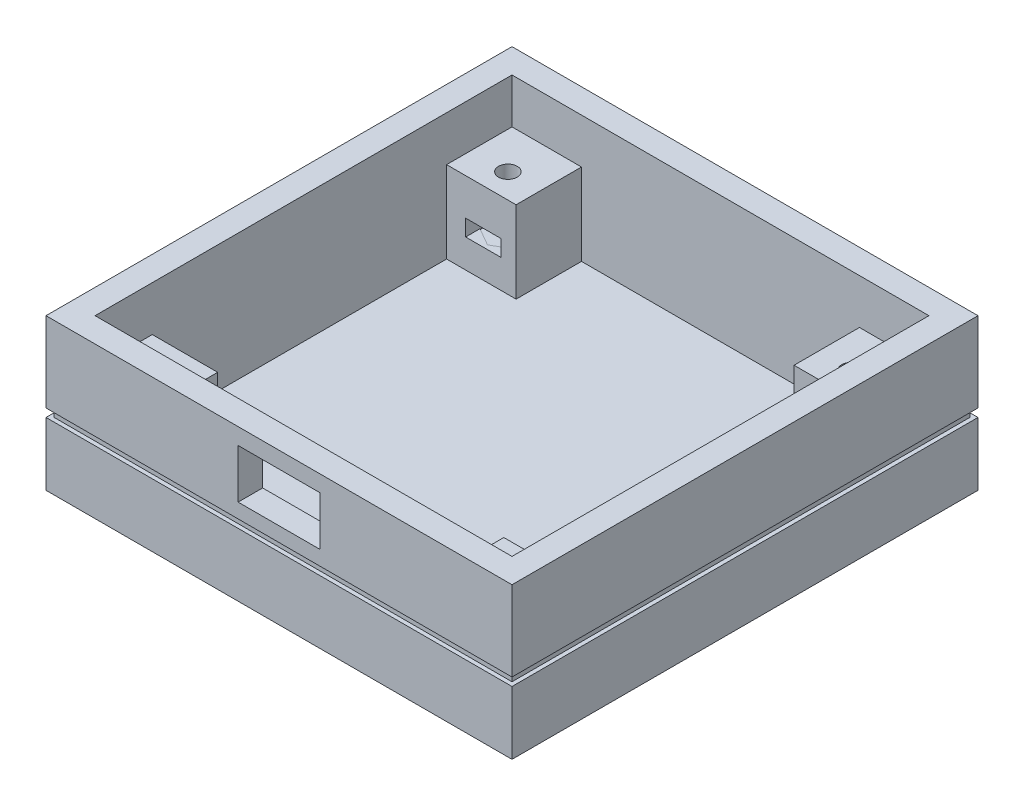
SolidWorks part; units mm, degrees
ref_plane "Plan de face" through (0, 0, 0) normal (0, 0, 1) x (1, 0, 0)
ref_plane "Plan de dessus" through (0, 0, 0) normal (0, 1, 0) x (1, 0, 0)
ref_plane "Plan de droite" through (0, 0, 0) normal (1, 0, 0) x (0, 0, -1)
sketch "Esquisse1" plane through (0, 0, 0) normal (0, 1, 0) x (1, 0, 0)
  line L1 (-30.0101, 36.8942) -> (26.9899, 36.8942)
  line L2 (-30.0101, 36.8942) -> (-30.0101, -20.1058)
  line L3 (-30.0101, -20.1058) -> (26.9899, -20.1058)
  line L4 (26.9899, 36.8942) -> (26.9899, -20.1058)
extrude "Boss.-Extru.1" add sketch "Esquisse1" along normal blind 18.5 contours L2 L3 L4 L1
sketch "Esquisse2" plane through (0, 18.5, 0) normal (0, 1, 0) x (1, 0, 0)
  line L0 (-30.0101, 36.8942) -> (26.9899, 36.8942) construction
  line L1 (-27.0101, 33.8942) -> (23.9899, 33.8942)
  line L2 (-27.0101, 33.8942) -> (-27.0101, -17.1058)
  line L3 (-27.0101, -17.1058) -> (23.9899, -17.1058)
  line L4 (23.9899, 33.8942) -> (23.9899, -17.1058)
  line L5 (-30.0101, 36.8942) -> (-30.0101, -20.1058) construction
  line L6 (26.9899, 36.8942) -> (26.9899, -20.1058) construction
  line L7 (-30.0101, -20.1058) -> (26.9899, -20.1058) construction
  dimension "D1" = 3
  dimension "D2" = 3
  dimension "D3" = 3
  dimension "D4" = 3
extrude "Enlèv. mat.-Extru.1" cut sketch "Esquisse2" against normal blind 15.5 contours L2 L3 L4 L1
sketch "Esquisse4" plane through (0, 3, 0) normal (0, 1, 0) x (1, 0, 0)
  line L1 (-18.5101, 25.8942) -> (-27.0101, 25.8942)
  line L2 (-18.5101, 25.8942) -> (-18.5101, 33.8942)
  line L3 (-18.5101, 33.8942) -> (-27.0101, 33.8942)
  line L4 (-27.0101, 25.8942) -> (-27.0101, 33.8942)
extrude "Boss.-Extru.2" add sketch "Esquisse4" along normal blind 10
sketch "Esquisse5" plane through (0, 3, 0) normal (0, 1, 0) x (1, 0, 0)
  line L1 (23.9899, 33.8942) -> (15.4899, 33.8942)
  line L2 (23.9899, 33.8942) -> (23.9899, 25.8942)
  line L3 (23.9899, 25.8942) -> (15.4899, 25.8942)
  line L4 (15.4899, 33.8942) -> (15.4899, 25.8942)
extrude "Boss.-Extru.3" add sketch "Esquisse5" along normal blind 10
sketch "Esquisse6" plane through (0, 3, 0) normal (0, 1, 0) x (1, 0, 0)
  line L1 (23.9899, -17.1058) -> (15.9899, -17.1058)
  line L2 (23.9899, -17.1058) -> (23.9899, -10.1058)
  line L3 (23.9899, -10.1058) -> (15.9899, -10.1058)
  line L4 (15.9899, -17.1058) -> (15.9899, -10.1058)
extrude "Boss.-Extru.4" add sketch "Esquisse6" along normal blind 10
sketch "Esquisse7" plane through (0, 3, 0) normal (0, 1, 0) x (1, 0, 0)
  line L1 (-19.0101, -10.1058) -> (-27.0101, -10.1058)
  line L2 (-19.0101, -10.1058) -> (-19.0101, -17.1058)
  line L3 (-19.0101, -17.1058) -> (-27.0101, -17.1058)
  line L4 (-27.0101, -10.1058) -> (-27.0101, -17.1058)
extrude "Boss.-Extru.5" add sketch "Esquisse7" along normal blind 10
sketch "Esquisse8" plane through (0, 13, 0) normal (0, 1, 0) x (1, 0, 0)
  line L0 (15.9899, -17.1058) -> (23.9899, -17.1058) construction
  line L2 (23.9899, -17.1058) -> (23.9899, -10.1058) construction
  circle A0 centre (19.4899, -13.1058) radius 1.15
  dimension "D1" = 4
  dimension "D2" = 4.5
extrude "Enlèv. mat.-Extru.2" cut sketch "Esquisse8" against normal blind 10
sketch "Esquisse9" plane through (0, 13, 0) normal (0, 1, 0) x (1, 0, 0)
  line L0 (-27.0101, -17.1058) -> (-19.0101, -17.1058) construction
  line L1 (-27.0101, -10.1058) -> (-27.0101, -17.1058) construction
  circle A0 centre (-22.5101, -13.1058) radius 1.15
  dimension "D1" = 4
  dimension "D2" = 4.5
extrude "Enlèv. mat.-Extru.3" cut sketch "Esquisse9" against normal blind 10
sketch "Esquisse16" plane through (0, 13, 0) normal (0, 1, 0) x (1, 0, 0)
  line L0 (-18.5101, 33.8942) -> (-27.0101, 33.8942) construction
  line L1 (-27.0101, 33.8942) -> (-27.0101, 25.8942) construction
  circle A0 centre (-22.5101, 28.8942) radius 1.15
  dimension "D1" = 5
  dimension "D2" = 4.5
extrude "Enlèv. mat.-Extru.9" cut sketch "Esquisse16" against normal blind 6.6 contours A0
sketch "Esquisse17" plane through (0, 13, 0) normal (0, 1, 0) x (1, 0, 0)
  line L0 (23.9899, 33.8942) -> (15.4899, 33.8942) construction
  line L1 (23.9899, 25.8942) -> (23.9899, 33.8942) construction
  circle A0 centre (19.4899, 28.8942) radius 1.15
  dimension "D1" = 5
  dimension "D2" = 4.5
extrude "Enlèv. mat.-Extru.10" cut sketch "Esquisse17" against normal blind 10
sketch "Esquisse21" plane through (0, 0, 20.1058) normal (0, 0, 1) x (1, 0, 0)
  line L0 (-30.0101, 0) -> (26.9899, 0) construction
  line L1 (-6.5101, 16.5) -> (3.4899, 16.5)
  line L2 (-6.5101, 16.5) -> (-6.5101, 10.5)
  line L3 (-6.5101, 10.5) -> (3.4899, 10.5)
  line L4 (3.4899, 16.5) -> (3.4899, 10.5)
  line L5 (-30.0101, 18.5) -> (-30.0101, 0) construction
  line L7 (26.9899, 18.5) -> (26.9899, 0) construction
  dimension "D1" = 10.5
  dimension "D2" = 23.5
  dimension "D3" = 23.5
extrude "Enlèv. mat.-Extru.14" cut sketch "Esquisse21" against normal blind 3
sketch "Esquisse23" plane through (0, 0, -25.8942) normal (0, 0, 1) x (1, 0, 0)
  line L0 (15.4899, 13) -> (15.4899, 3) construction
  line L5 (21.6599, 5) -> (17.3199, 5)
  line L6 (21.6599, 5) -> (21.6599, 3)
  line L7 (21.6599, 3) -> (17.3199, 3)
  line L8 (17.3199, 5) -> (17.3199, 3)
  line L9 (23.9899, 13) -> (23.9899, 3) construction
  dimension "D1" = 1.83
  dimension "D2" = 2.33
sketch "Esquisse24" plane through (0, 13, 0) normal (0, 1, 0) x (1, 0, 0)
  line L1 (19.4899, 26.3942) -> (21.655, 27.6442)
  line L2 (21.655, 27.6442) -> (21.655, 30.1442)
  line L3 (21.655, 30.1442) -> (19.4899, 31.3942)
  line L4 (19.4899, 31.3942) -> (17.3249, 30.1442)
  line L5 (17.3249, 30.1442) -> (17.3249, 27.6442)
  line L6 (17.3249, 27.6442) -> (19.4899, 26.3942)
  circle A0 centre (19.4899, 28.8942) radius 2.1651 construction
  circle A1 centre (19.4899, 28.8942) radius 1.15 construction
  dimension "D1" = 0
extrude "Enlèv. mat.-Extru.18" cut sketch "Esquisse24" against normal blind 2 from offset 8 contours L1 L2 L3 L4 L5 L6 offset against normal yes
sketch "Esquisse25" plane through (0, 13, 0) normal (0, 1, 0) x (1, 0, 0)
  line L1 (17.3249, -11.8558) -> (17.3249, -14.3558)
  line L2 (17.3249, -14.3558) -> (19.4899, -15.6058)
  line L3 (19.4899, -15.6058) -> (21.655, -14.3558)
  line L4 (21.655, -14.3558) -> (21.655, -11.8558)
  line L5 (21.655, -11.8558) -> (19.4899, -10.6058)
  line L6 (19.4899, -10.6058) -> (17.3249, -11.8558)
  circle A0 centre (19.4899, -13.1058) radius 2.1651 construction
  circle A1 centre (19.4899, -13.1058) radius 1.15 construction
  dimension "D1" = 0
extrude "Enlèv. mat.-Extru.20" cut sketch "Esquisse25" against normal blind 2 from offset 8 offset against normal yes
sketch "Esquisse26" plane through (0, 0, 10.1058) normal (0, 0, -1) x (-1, 0, 0)
  line L0 (-15.9899, 13) -> (-15.9899, 3) construction
  line L1 (-21.6599, 5) -> (-17.3199, 5)
  line L2 (-21.6599, 5) -> (-21.6599, 3)
  line L3 (-21.6599, 3) -> (-17.3199, 3)
  line L4 (-17.3199, 5) -> (-17.3199, 3)
  line L5 (-23.9899, 13) -> (-23.9899, 3) construction
  dimension "D1" = 1.33
  dimension "D2" = 2.33
extrude "Enlèv. mat.-Extru.21" cut sketch "Esquisse26" against normal blind 2.848
sketch "Esquisse27" plane through (0, 13, 0) normal (0, 1, 0) x (1, 0, 0)
  line L1 (-20.345, 27.6442) -> (-20.345, 30.1442)
  line L2 (-20.345, 30.1442) -> (-22.5101, 31.3942)
  line L3 (-22.5101, 31.3942) -> (-24.6751, 30.1442)
  line L4 (-24.6751, 30.1442) -> (-24.6751, 27.6442)
  line L5 (-24.6751, 27.6442) -> (-22.5101, 26.3942)
  line L6 (-22.5101, 26.3942) -> (-20.345, 27.6442)
  circle A0 centre (-22.5101, 28.8942) radius 2.1651 construction
  circle A1 centre (-22.5101, 28.8942) radius 1.15 construction
  dimension "D1" = 0
  dimension "D2" = 0
extrude "Enlèv. mat.-Extru.22" cut sketch "Esquisse27" against normal blind 2.1 from offset 4.5 contours L4 L5 L6 L1 L2 L3 offset against normal yes
sketch "Esquisse29" plane through (0, 13, 0) normal (0, 1, 0) x (1, 0, 0)
  line L1 (-20.345, -11.8558) -> (-22.5101, -10.6058)
  line L2 (-22.5101, -10.6058) -> (-24.6751, -11.8558)
  line L3 (-24.6751, -11.8558) -> (-24.6751, -14.3558)
  line L4 (-24.6751, -14.3558) -> (-22.5101, -15.6058)
  line L5 (-22.5101, -15.6058) -> (-20.345, -14.3558)
  line L6 (-20.345, -14.3558) -> (-20.345, -11.8558)
  circle A0 centre (-22.5101, -13.1058) radius 2.1651 construction
  circle A1 centre (-22.5101, -13.1058) radius 1.15 construction
  dimension "D1" = 0
extrude "Enlèv. mat.-Extru.24" cut sketch "Esquisse29" against normal blind 2 from offset 8 offset against normal yes
sketch "Esquisse30" plane through (0, 0, 10.1058) normal (0, 0, -1) x (-1, 0, 0)
  line L0 (19.0101, 13) -> (19.0101, 3) construction
  line L1 (24.6801, 5) -> (20.3401, 5)
  line L2 (24.6801, 5) -> (24.6801, 3)
  line L3 (24.6801, 3) -> (20.3401, 3)
  line L4 (20.3401, 5) -> (20.3401, 3)
  line L5 (27.0101, 13) -> (27.0101, 3) construction
  dimension "D1" = 1.33
  dimension "D2" = 2.33
extrude "Enlèv. mat.-Extru.26" cut sketch "Esquisse23" against normal blind 2 contours L5 L8 L7 L6
sketch "Esquisse31" plane through (0, 0, -25.8942) normal (0, 0, 1) x (1, 0, 0)
  line L0 (-27.0101, 13) -> (-27.0101, 3) construction
  line L1 (-24.6801, 8.5) -> (-20.3401, 8.5)
  line L2 (-24.6801, 8.5) -> (-24.6801, 6.5)
  line L3 (-24.6801, 6.5) -> (-20.3401, 6.5)
  line L4 (-20.3401, 8.5) -> (-20.3401, 6.5)
  line L5 (-27.0101, 13) -> (-18.5101, 13) construction
  line L6 (-18.5101, 13) -> (-18.5101, 3) construction
  dimension "D1" = 2.33
  dimension "D2" = 1.83
  dimension "D3" = 4.5
extrude "Enlèv. mat.-Extru.27" cut sketch "Esquisse31" against normal blind 2 contours L1 L4 L3 L2
extrude "Enlèv. mat.-Extru.28" cut sketch "Esquisse30" against normal blind 2 contours L1 L4 L3 L2
sketch "Esquisse32" plane through (-30.0101, 0, 0) normal (-1, 0, 0) x (0, 0, 1)
  line L0 (20.1058, 18.5) -> (20.1058, 0) construction
  line L1 (20.1058, 8.72) -> (-36.8942, 8.72)
  line L2 (20.1058, 8.72) -> (20.1058, 7.72)
  line L3 (20.1058, 7.72) -> (-36.8942, 7.72)
  line L4 (-36.8942, 8.72) -> (-36.8942, 7.72)
  line L5 (-36.8942, 18.5) -> (-36.8942, 0) construction
sketch "Esquisse33" plane through (0, 0, 20.1058) normal (0, 0, 1) x (1, 0, 0)
  line L0 (26.9899, 18.5) -> (26.9899, 0) construction
  line L1 (-30.0101, 8.72) -> (26.9899, 8.72)
  line L2 (-30.0101, 8.72) -> (-30.0101, 7.72)
  line L3 (-30.0101, 7.72) -> (26.9899, 7.72)
  line L4 (26.9899, 8.72) -> (26.9899, 7.72)
extrude "Enlèv. mat.-Extru.29" cut sketch "Esquisse32" against normal blind 0.5
extrude "Enlèv. mat.-Extru.30" cut sketch "Esquisse33" against normal blind 0.5 contours L1 L4 L3 L2
sketch "Esquisse34" plane through (26.9899, 0, 0) normal (1, 0, 0) x (0, 0, -1)
  line L0 (36.8942, 18.5) -> (36.8942, 0) construction
  line L1 (-20.1058, 7.72) -> (36.8942, 7.72)
  line L2 (-20.1058, 7.72) -> (-20.1058, 8.72)
  line L3 (-20.1058, 8.72) -> (36.8942, 8.72)
  line L4 (36.8942, 7.72) -> (36.8942, 8.72)
extrude "Enlèv. mat.-Extru.31" cut sketch "Esquisse34" against normal blind 0.5
sketch "Esquisse35" plane through (0, 0, -36.8942) normal (0, 0, -1) x (-1, 0, 0)
  line L0 (29.5101, 8.72) -> (30.0101, 8.72) construction
  line L1 (-26.9899, 7.72) -> (30.0101, 7.72)
  line L2 (-26.9899, 7.72) -> (-26.9899, 8.72)
  line L3 (-26.9899, 8.72) -> (30.0101, 8.72)
  line L4 (30.0101, 7.72) -> (30.0101, 8.72)
  line L5 (30.0101, 18.5) -> (30.0101, 8.72) construction
extrude "Enlèv. mat.-Extru.32" cut sketch "Esquisse35" against normal blind 0.5
